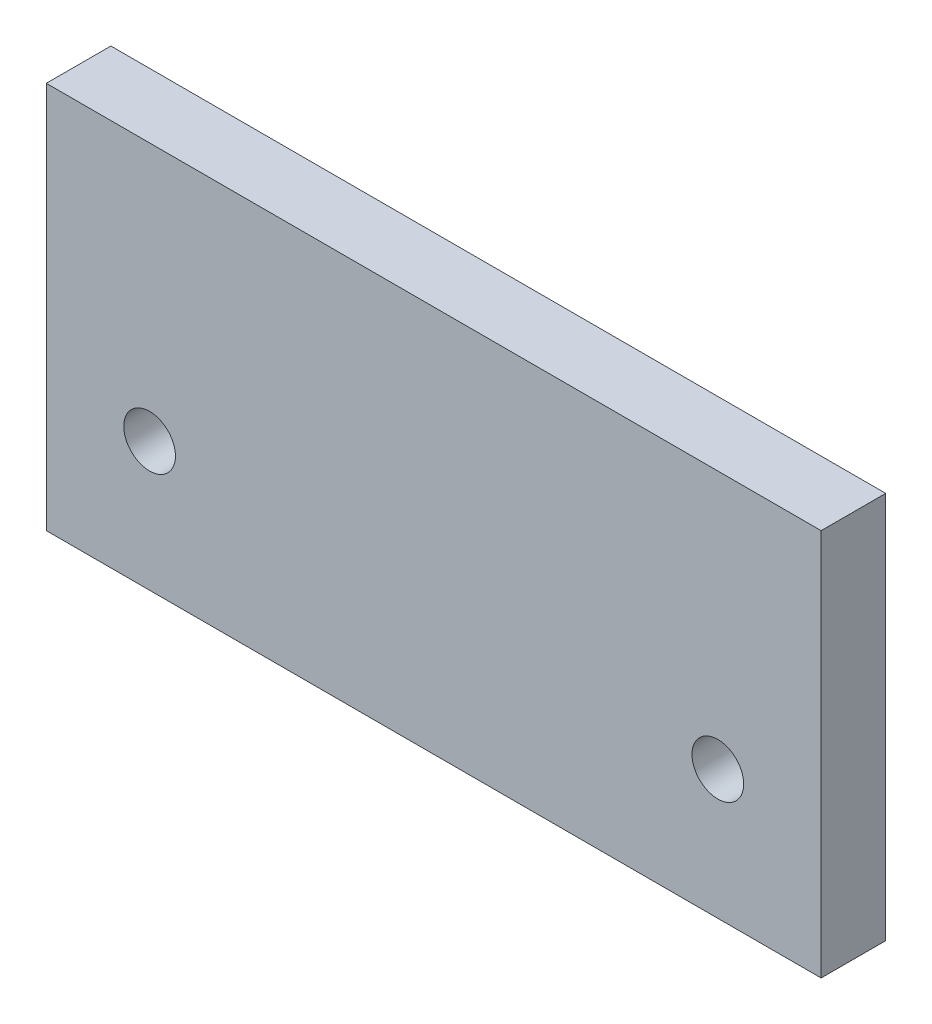
SolidWorks part; units mm, degrees
ref_plane "Front Plane" through (0, 0, 0) normal (0, 0, 1) x (1, 0, 0)
ref_plane "Top Plane" through (0, 0, 0) normal (0, 1, 0) x (1, 0, 0)
ref_plane "Right Plane" through (0, 0, 0) normal (1, 0, 0) x (0, 0, -1)
sketch "Sketch1" plane through (0, 0, 0) normal (0, 0, 1) x (1, 0, 0)
  line L0 (-17.5538, 8.5694) -> (-17.5538, -58.4469) construction
  line L1 (-47.5538, 8.5694) -> (12.4462, 8.5694)
  line L2 (-47.5538, 8.5694) -> (-47.5538, -21.4306)
  line L3 (-47.5538, -21.4306) -> (12.4462, -21.4306)
  line L4 (12.4462, 8.5694) -> (12.4462, -21.4306)
  circle A0 centre (-39.5538, -11.4306) radius 2
  circle A1 centre (4.4462, -11.4306) radius 2
  dimension "D3" = 4
  dimension "D4" = 22
  dimension "D1" = 60
  dimension "D2" = 30
  dimension "D5" = 20
  dimension "D6" = 30
extrude "Boss-Extrude1" add sketch "Sketch1" along normal blind 5
